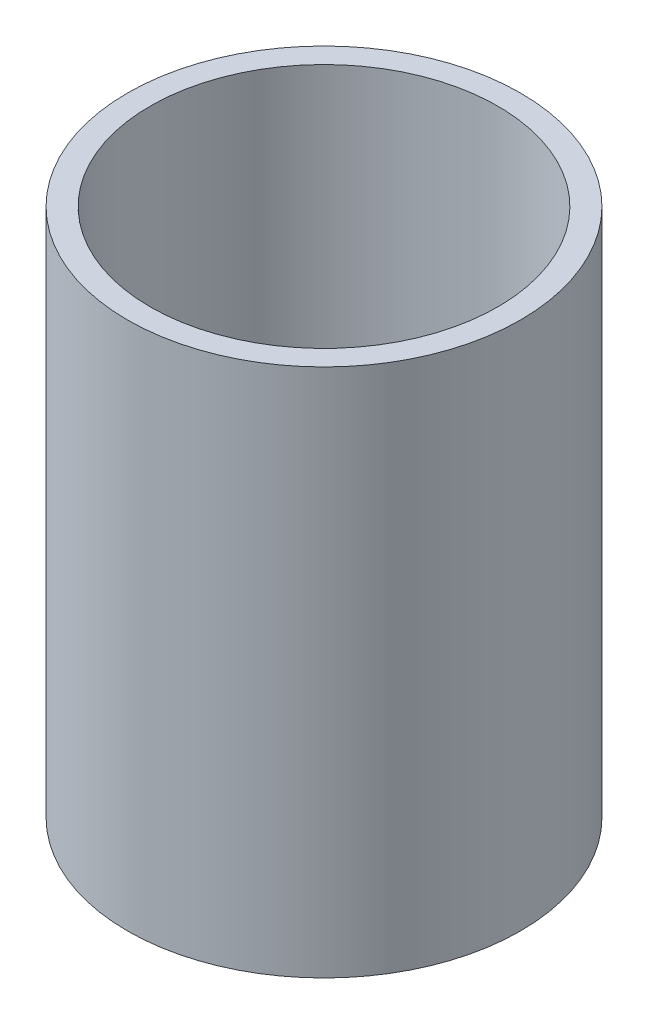
SolidWorks part; units mm, degrees
ref_plane "Front Plane" through (0, 0, 0) normal (0, 0, 1) x (1, 0, 0)
ref_plane "Top Plane" through (0, 0, 0) normal (0, 1, 0) x (1, 0, 0)
ref_plane "Right Plane" through (0, 0, 0) normal (1, 0, 0) x (0, 0, -1)
sketch "Sketch1" plane through (0, 0, 0) normal (0, 1, 0) x (1, 0, 0)
  circle A0 centre (0, 0) radius 23
  circle A1 centre (0, 0) radius 26
  dimension "D1" = 52
  dimension "D2" = 46
extrude "Boss-Extrude1" add sketch "Sketch1" along normal blind 70
